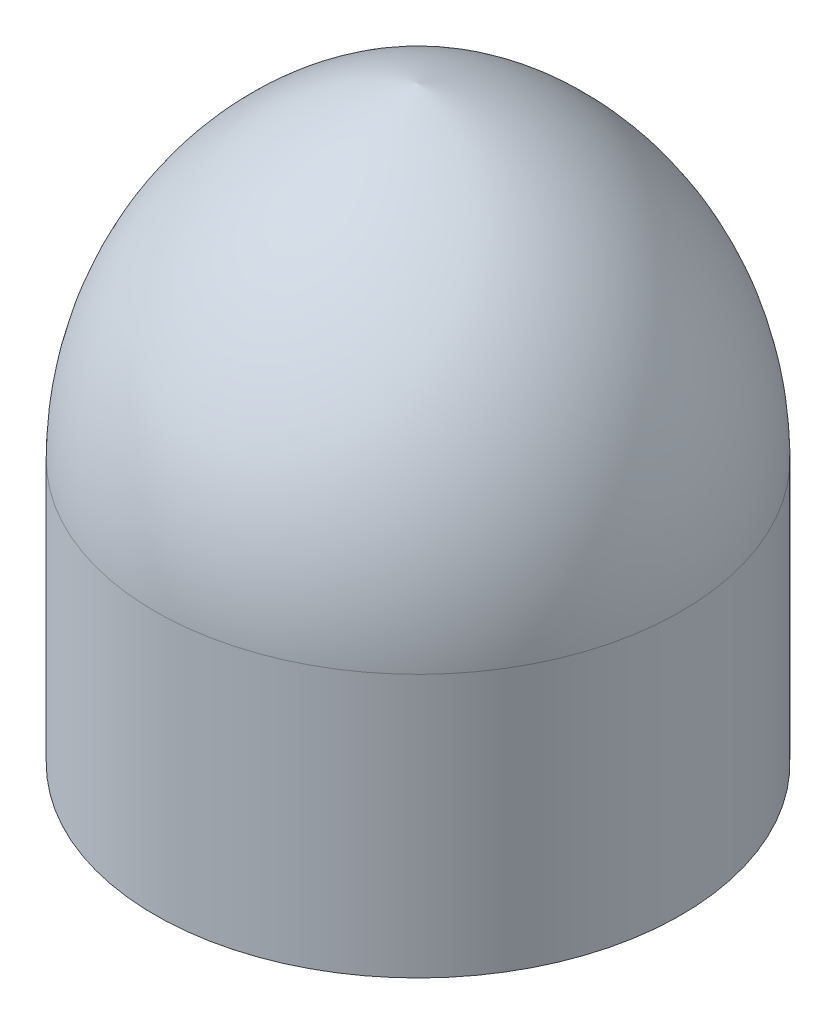
SolidWorks part; units mm, degrees
ref_plane "Front Plane" through (0, 0, 0) normal (0, 0, 1) x (1, 0, 0)
ref_plane "Top Plane" through (0, 0, 0) normal (0, 1, 0) x (1, 0, 0)
ref_plane "Right Plane" through (0, 0, 0) normal (1, 0, 0) x (0, 0, -1)
sketch "Sketch1" plane through (0, 0, 0) normal (0, 0, 1) x (1, 0, 0)
  line L0 (0, 7.62) -> (0, 17.0557)
  line L1 (0, 0) -> (7.62, 0)
  line L2 (0, 0) -> (0, 7.62)
  line L4 (7.62, 0) -> (7.62, 7.62)
  arc A0 (7.62, 7.62) -> (0, 17.0557) centre (-2.032, 7.62) ccw
  dimension "D3" = 9.652
  dimension "D1" = 7.62
  dimension "D2" = 7.62
revolve "Revolve1" add sketch "Sketch1" angle 360 about L0
sketch "Sketch2" plane through (0, 0, 0) normal (0, -1, 0) x (1, 0, 0)
  circle A0 centre (0, 0) radius 3.175
  dimension "D1" = 6.35
extrude "Cut-Extrude1" cut sketch "Sketch2" against normal blind 12.7
